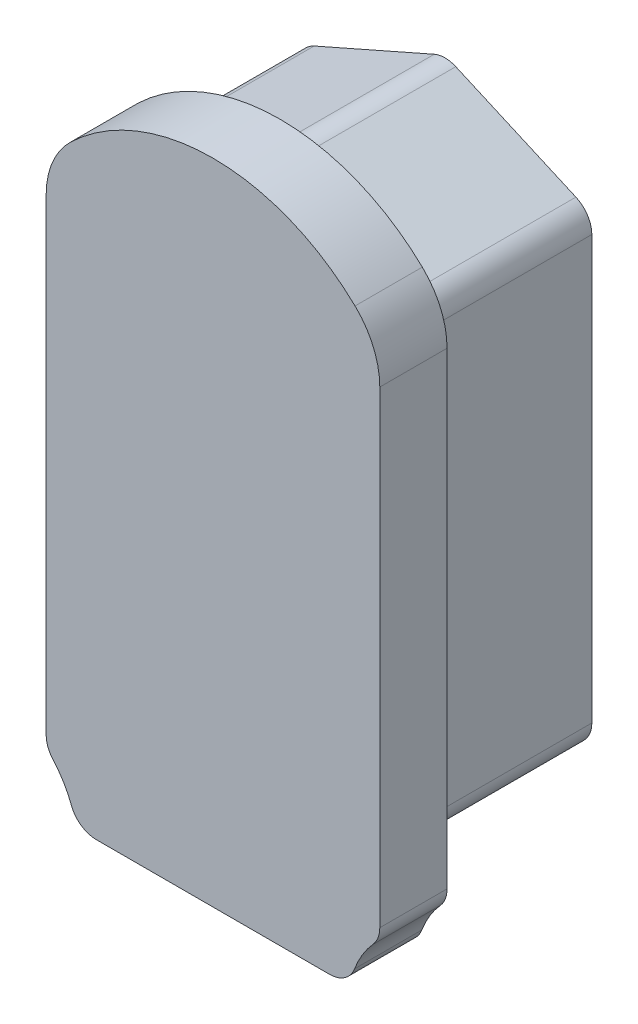
SolidWorks part; units mm, degrees
ref_plane "Přední rovina" through (0, 0, 0) normal (0, 0, 1) x (1, 0, 0)
ref_plane "Horní rovina" through (0, 0, 0) normal (0, 1, 0) x (1, 0, 0)
ref_plane "Pravá rovina" through (0, 0, 0) normal (1, 0, 0) x (0, 0, -1)
sketch "Skica1" plane through (0, 0, 0) normal (0, 0, 1) x (1, 0, 0)
  line L1 (6.25, -12.15) -> (-6.25, -12.15)
  line L2 (6.25, -12.15) -> (6.25, 12.15)
  line L3 (6.25, 12.15) -> (-6.25, 12.15)
  line L4 (-6.25, -12.15) -> (-6.25, 12.15)
  line L5 (6.25, -12.15) -> (-6.25, 12.15) construction
  line L6 (6.25, 12.15) -> (-6.25, -12.15) construction
  point P0 (0, 0)
  dimension "D1" = 12.5
  dimension "D2" = 24.3
extrude "Přidat vysunutím1" add sketch "Skica1" along normal blind 4.52
sketch "Skica2" plane through (0, 0, 0) normal (0, 0, -1) x (-1, 0, 0)
  line L1 (-6.25, 12.15) -> (6.25, 12.15) construction
  line L2 (6.25, 12.15) -> (6.25, -12.15) construction
  line L3 (-6.25, -12.15) -> (-6.25, 12.15) construction
  line L4 (-6.25, 8.95) -> (-6.25, 12.15)
  line L5 (-6.25, 12.15) -> (6.25, 12.15)
  line L6 (6.25, 12.15) -> (6.25, 8.95)
  arc A0 (6.25, 8.95) -> (-6.25, 8.95) centre (0, 4.4465) ccw
  line M2 (6.25, -12.15) -> (6.25, 12.15)
  line M3 (6.25, 12.15) -> (-6.25, 12.15)
  line M4 (-6.25, 12.15) -> (-6.25, -12.15)
extrude "Odebrat vysunutím1" cut sketch "Skica2" against normal blind 4.52 contours A0 L5 M4 | A0 M2 M3
sketch "Skica3" plane through (0, 0, 0) normal (0, 0, -1) x (-1, 0, 0)
  line L0 (-6.25, -10.1059) -> (-6.25, -12.15)
  line L1 (-6.25, -12.15) -> (-6.25, 8.95) construction
  line L2 (-6.25, -12.15) -> (-5.1303, -12.15)
  line L3 (6.25, -12.15) -> (-6.25, -12.15) construction
  line L4 (0, 0) -> (0, -12.15) construction
  line L5 (6.25, -12.15) -> (5.1303, -12.15)
  line L6 (6.25, -10.1059) -> (6.25, -12.15)
  arc A0 (-5.1303, -12.15) -> (-6.25, -10.1059) centre (-8.6677, -12.7589) ccw
  arc A1 (5.1303, -12.15) -> (6.25, -10.1059) centre (8.6677, -12.7589) cw
extrude "Odebrat vysunutím2" cut sketch "Skica3" against normal blind 4.52
fillet "Zaoblit1" radius 1 4 edges at (-6.25, -10.1059, 2.26) (-5.1303, -12.15, 2.26) (5.1303, -12.15, 2.26) (6.25, -10.1059, 2.26)
fillet "Zaoblit2" radius 3 2 edges at (6.25, 8.95, 2.26) (-6.25, 8.95, 2.26)
sketch "Skica4" plane through (0, 0, 0) normal (0, 0, -1) x (-1, 0, 0)
  line L0 (0, 11.15) -> (-5.5, 8.7268)
  line L1 (-5.5, 8.7268) -> (-5.5, -8.4268)
  line L2 (-5.5, -8.4268) -> (0, -10.85)
  line L3 (0, -10.85) -> (5.5, -8.4268)
  line L4 (5.5, -8.4268) -> (5.5, 8.7268)
  line L5 (5.5, 8.7268) -> (0, 11.15)
  line L6 (-5.5, 8.7268) -> (5.5, 8.7268) construction
  line L7 (-5.5, -8.4268) -> (5.5, -8.4268) construction
  line L8 (0, 0) -> (0, 1.0593) construction
  arc A0 (5.3229, 10.0152) -> (-5.3229, 10.0152) centre (0, 4.4465) ccw construction
  point P12 (0, 12.15)
  dimension "D1" = 11
  dimension "D2" = 22
  dimension "D3" = 1
extrude "Přidat vysunutím2" add sketch "Skica4" along normal blind 6.174
fillet "Zaoblit4" radius 1 6 edges at (0, 11.15, -3.087) (-5.5, 8.7268, -3.087) (-5.5, -8.4268, -3.087) (0, -10.85, -3.087) (5.5, -8.4268, -3.087) (5.5, 8.7268, -3.087)
sketch "Skica5" plane through (0, 0, 4.52) normal (0, 0, 1) x (1, 0, 0)
  line L3 (6.25, -9.6959) -> (6.25, 7.8466)
  line L4 (-6.25, 7.8466) -> (-6.25, -9.6959)
  line L5 (-4.3696, -12.15) -> (4.3696, -12.15)
  line L6 (6.25, -9.6959) -> (6.25, 7.8466)
  line L7 (-6.25, 7.8466) -> (-6.25, -9.6959)
  line L8 (-4.3696, -12.15) -> (4.3696, -12.15)
  arc A9 (6.25, 7.8466) -> (5.3229, 10.0152) centre (3.25, 7.8466) ccw
  arc A10 (5.3229, 10.0152) -> (-5.3229, 10.0152) centre (0, 4.4465) ccw
  arc A11 (-5.3229, 10.0152) -> (-6.25, 7.8466) centre (-3.25, 7.8466) ccw
  arc A12 (-6.25, -9.6959) -> (-5.9947, -10.3633) centre (-5.25, -9.6959) ccw
  arc A13 (-5.3061, -11.5006) -> (-5.9947, -10.3633) centre (-8.6677, -12.7589) ccw
  arc A14 (-5.3061, -11.5006) -> (-4.3696, -12.15) centre (-4.3696, -11.15) ccw
  arc A15 (4.3696, -12.15) -> (5.3061, -11.5006) centre (4.3696, -11.15) ccw
  arc A16 (5.9947, -10.3633) -> (5.3061, -11.5006) centre (8.6677, -12.7589) ccw
  arc A17 (5.9947, -10.3633) -> (6.25, -9.6959) centre (5.25, -9.6959) ccw
  arc A18 (6.25, 7.8466) -> (5.3229, 10.0152) centre (3.25, 7.8466) ccw
  arc A19 (5.3229, 10.0152) -> (-5.3229, 10.0152) centre (0, 4.4465) ccw
  arc A20 (-5.3229, 10.0152) -> (-6.25, 7.8466) centre (-3.25, 7.8466) ccw
  arc A21 (-6.25, -9.6959) -> (-5.9947, -10.3633) centre (-5.25, -9.6959) ccw
  arc A22 (-5.3061, -11.5006) -> (-5.9947, -10.3633) centre (-8.6677, -12.7589) ccw
  arc A23 (-5.3061, -11.5006) -> (-4.3696, -12.15) centre (-4.3696, -11.15) ccw
  arc A24 (4.3696, -12.15) -> (5.3061, -11.5006) centre (4.3696, -11.15) ccw
  arc A25 (5.9947, -10.3633) -> (5.3061, -11.5006) centre (8.6677, -12.7589) ccw
  arc A26 (5.9947, -10.3633) -> (6.25, -9.6959) centre (5.25, -9.6959) ccw
  dimension "D1" = 0
extrude "Odebrat vysunutím3" cut sketch "Skica5" against normal blind 2
